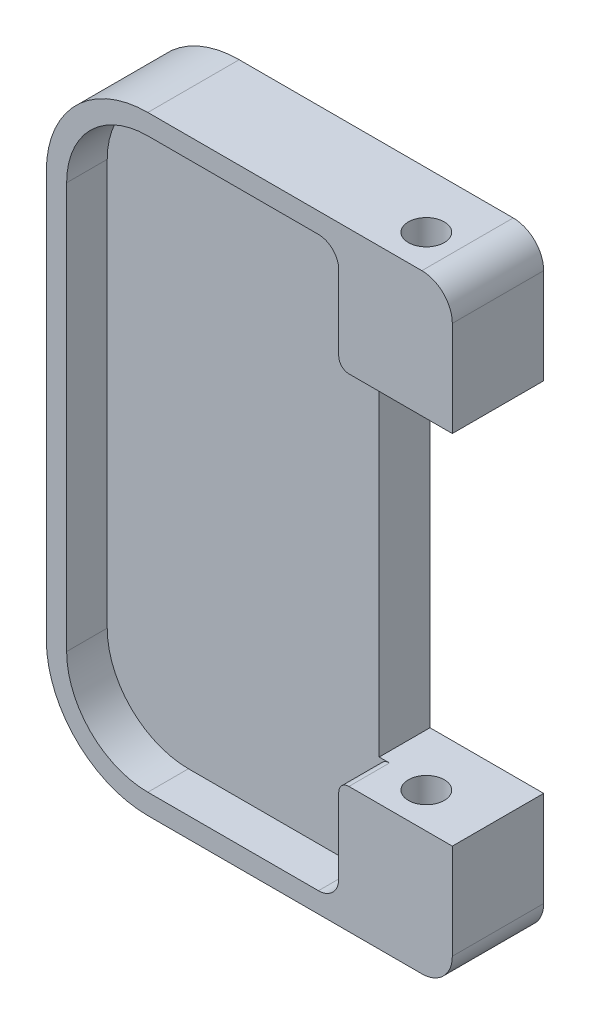
SolidWorks part; units mm, degrees
ref_plane "Front Plane" through (0, 0, 0) normal (0, 0, 1) x (1, 0, 0)
ref_plane "Top Plane" through (0, 0, 0) normal (0, 1, 0) x (1, 0, 0)
ref_plane "Right Plane" through (0, 0, 0) normal (1, 0, 0) x (0, 0, -1)
sketch "Sketch1" plane through (0, 0, 0) normal (0, 0, 1) x (1, 0, 0)
  line L1 (57.15, -22.225) -> (-57.15, -22.225)
  line L2 (57.15, -22.225) -> (57.15, 22.225)
  line L3 (57.15, 22.225) -> (-57.15, 22.225)
  line L4 (-57.15, -22.225) -> (-57.15, 22.225)
  line L5 (57.15, -22.225) -> (-57.15, 22.225) construction
  line L6 (57.15, 22.225) -> (-57.15, -22.225) construction
  point P0 (0, 0)
  dimension "D1" = 44.45
  dimension "D2" = 114.3
extrude "Boss-Extrude1" add sketch "Sketch1" along normal blind 62.23
sketch "Sketch2" plane through (0, 0, 62.23) normal (0, 0, 1) x (1, 0, 0)
  line L0 (-57.15, 22.225) -> (-57.15, -22.225) construction
  line L1 (57.15, -15.025) -> (-57.15, -15.025)
  line L2 (57.15, -15.025) -> (57.15, 15.025)
  line L3 (57.15, 15.025) -> (-57.15, 15.025)
  line L4 (-57.15, -15.025) -> (-57.15, 15.025)
  line L5 (57.15, -15.025) -> (-57.15, 15.025) construction
  line L6 (57.15, 15.025) -> (-57.15, -15.025) construction
  line L7 (57.15, 22.225) -> (-57.15, 22.225) construction
  point P0 (0, 0)
  dimension "D1" = 7.2
extrude "Cut-Extrude2" cut sketch "Sketch2" against normal blind 31.75
sketch "Sketch3" plane through (0, 0, 0) normal (0, 0, -1) x (-1, 0, 0)
  line L0 (-57.15, -22.225) -> (-57.15, 22.225) construction
  line L1 (57.15, 22.225) -> (-57.15, 22.225)
  line L2 (57.15, 22.225) -> (57.15, -9.525)
  line L3 (57.15, -9.525) -> (-57.15, -9.525)
  line L4 (-57.15, 22.225) -> (-57.15, -9.525)
  line L5 (57.15, -22.225) -> (-57.15, -22.225) construction
  dimension "D1" = 12.7
extrude "Cut-Extrude3" cut sketch "Sketch3" against normal blind 21.59
sketch "Sketch7" plane through (0, -22.225, 0) normal (0, -1, 0) x (1, 0, 0)
  line L0 (57.15, 62.23) -> (57.15, 0) construction
  line L1 (-57.15, 0) -> (57.15, 0) construction
  circle A0 centre (31.75, 50.36) radius 4.8
  circle A1 centre (-27.14, 39.37) radius 4.8
  dimension "D1" = 9.6
  dimension "D2" = 25.4
  dimension "D3" = 39.37
  dimension "D4" = 9.6
  dimension "D5" = 58.89
  dimension "D6" = 10.99
extrude "Cut-Extrude6" cut sketch "Sketch7" against normal up to surface (44.45 mm away) up to face at (0, 22.225, 41.91)
sketch "Sketch9" plane through (0, 0, 30.48) normal (0, 0, 1) x (1, 0, 0)
  line L5 (57.15, 15.025) -> (-57.15, 15.025) construction
  line L6 (-38.1, 15.025) -> (6.35, 15.025)
  line L7 (-38.1, 15.025) -> (-38.1, -15.025)
  line L8 (-38.1, -15.025) -> (6.35, -15.025)
  line L9 (6.35, 15.025) -> (6.35, -15.025)
  line L10 (-57.15, -15.025) -> (57.15, -15.025) construction
  line L11 (-57.15, 15.025) -> (-57.15, -15.025) construction
  line L12 (57.15, -15.025) -> (57.15, 15.025) construction
  dimension "D1" = 50.8
  dimension "25in" = 19.05
extrude "Cut-Extrude7" cut sketch "Sketch9" against normal through all both and the other way through all
sketch "Sketch16" plane through (0, -22.225, 0) normal (0, -1, 0) x (1, 0, 0)
  line L1 (-38.1, 30.48) -> (-57.15, 30.48) construction
  line L8 (-57.15, 62.23) -> (57.15, 62.23)
  line L9 (57.15, 62.23) -> (57.15, 47.0103)
  line L10 (57.15, 62.23) -> (57.15, 0) construction
  line L11 (-15.99, 39.37) -> (21.87, 50.36)
  line L12 (41.63, 50.36) -> (57.15, 47.0103)
  line L13 (-48.4121, 30.48) -> (-57.15, 30.48)
  line L15 (-57.15, 30.48) -> (-57.15, 62.23)
  arc A2 (41.63, 50.36) -> (21.87, 50.36) centre (31.75, 50.36) ccw
  arc A3 (-15.99, 39.37) -> (-38.2702, 40.0345) centre (-27.14, 39.37) ccw
  circle A4 centre (-27.14, 39.37) radius 4.8 construction
  circle A5 centre (31.75, 50.36) radius 4.8 construction
  arc A6 (-48.4121, 30.48) -> (-38.2702, 40.0345) centre (-48.4121, 40.64) ccw
  dimension "D1" = 6.35
  dimension "D2" = 5.08
  dimension "D3" = 10.16
extrude "Cut-Extrude8" cut sketch "Sketch16" against normal through all
sketch "Sketch14" plane through (6.35, 0, 0) normal (-1, 0, 0) x (0, 0, 1)
  line L0 (0, -15.025) -> (30.48, -15.025) construction
  line L1 (21.59, -9.525) -> (0, -9.525)
  line L2 (21.59, -9.525) -> (21.59, -15.025)
  line L3 (21.59, -15.025) -> (0, -15.025)
  line L4 (0, -9.525) -> (0, -15.025)
extrude "Boss-Extrude2" add sketch "Sketch14" along normal up to next
sketch "Sketch17" plane through (0, 0, 21.59) normal (0, 0, 1) x (1, 0, 0)
  line L1 (6.35, -15.025) -> (-38.1, -15.025)
  line L2 (6.35, -15.025) -> (6.35, -9.525)
  line L3 (6.35, -9.525) -> (-38.1, -9.525)
  line L4 (-38.1, -15.025) -> (-38.1, -9.525)
extrude "Boss-Extrude3" add sketch "Sketch17" along normal up to surface (8.89 mm away) up to face at (31.75, 0, 30.48)
sketch "Sketch18" plane through (-57.15, 0, 0) normal (-1, 0, 0) x (0, 0, 1)
  line L0 (30.48, 22.225) -> (30.48, -22.225) construction
  line L1 (21.59, 22.225) -> (30.48, 22.225)
  line L2 (21.59, 22.225) -> (21.59, -22.225)
  line L3 (21.59, -22.225) -> (30.48, -22.225)
  line L4 (30.48, 22.225) -> (30.48, -22.225)
  line L5 (21.59, 22.225) -> (30.48, -22.225) construction
  line L6 (21.59, -22.225) -> (30.48, 22.225) construction
  line L7 (30.48, -22.225) -> (0, -22.225) construction
  line L8 (21.59, -9.525) -> (21.59, 22.225) construction
  line L9 (30.48, 22.225) -> (21.59, 22.225) construction
  point P0 (26.035, 0)
sketch "Sketch20" plane through (0, 0, 21.59) normal (0, 0, -1) x (-1, 0, 0)
  line L0 (38.1, 15.025) -> (38.1, -9.525) construction
  line L1 (38.1, 38.1) -> (88.9, 38.1)
  line L2 (38.1, 38.1) -> (38.1, -38.1)
  line L3 (38.1, -38.1) -> (88.9, -38.1)
  line L4 (88.9, 38.1) -> (88.9, -38.1)
  line L5 (38.1, 38.1) -> (88.9, -38.1) construction
  line L6 (38.1, -38.1) -> (88.9, 38.1) construction
  point P0 (63.5, 0)
  point P9 (88.9, 0)
  dimension "D1" = 76.2
  dimension "D2" = 50.8
extrude "Boss-Extrude5" add sketch "Sketch20" against normal up to vertex (8.89 mm away)
fillet "Fillet4" radius 12.7 2 edges at (-88.9, -38.1, 26.035) (-88.9, 38.1, 26.035)
sketch "Sketch21" plane through (0, 0, 30.48) normal (0, 0, 1) x (1, 0, 0)
  line L0 (-40.64, -35.56) -> (-40.64, -24.765)
  line L9 (-76.2, -35.56) -> (-40.64, -35.56)
  line L16 (-50.9521, -12.485) -> (-40.64, -12.485)
  line L17 (-40.64, -12.485) -> (-40.64, -12.065)
  line L21 (-76.2, -35.56) -> (-40.64, -35.56)
  line L22 (-40.64, -35.56) -> (-40.64, -24.765)
  line L23 (-40.64, -24.765) -> (-50.9521, -24.765)
  line L24 (-40.64, -24.765) -> (-50.9521, -24.765)
  line L25 (-50.9521, -24.765) -> (-50.9521, -12.485)
  line L26 (-50.9521, -24.765) -> (-50.9521, -12.485)
  line L27 (-50.9521, 12.485) -> (-50.9521, 24.765)
  line L28 (-50.9521, 12.485) -> (-50.9521, 24.765)
  line L29 (-50.9521, 24.765) -> (-40.64, 24.765)
  line L30 (-50.9521, 24.765) -> (-40.64, 24.765)
  line L31 (-40.64, 24.765) -> (-40.64, 35.56)
  line L32 (-40.64, 24.765) -> (-40.64, 35.56)
  line L33 (-40.64, 35.56) -> (-76.2, 35.56)
  line L36 (-50.9521, -12.485) -> (54.61, -12.485)
  line L37 (54.61, -12.485) -> (54.61, 12.485)
  line L38 (54.61, 12.485) -> (8.89, 12.485)
  line L39 (8.89, 12.485) -> (8.89, -12.065)
  line L40 (8.89, -12.065) -> (-40.64, -12.065)
  line L41 (-40.64, -12.065) -> (-40.64, 12.485)
  line L42 (-40.64, 12.485) -> (-50.9521, 12.485)
  line L43 (-40.64, 35.56) -> (-76.2, 35.56)
  line L44 (-86.36, 25.4) -> (-86.36, -25.4)
  line L45 (-86.36, 25.4) -> (-86.36, -25.4)
  line L57 (-40.64, -12.065) -> (-40.64, 12.485)
  line L58 (-40.64, 12.485) -> (-50.9521, 12.485)
  arc A9 (-76.2, 35.56) -> (-86.36, 25.4) centre (-76.2, 25.4) ccw
  arc A10 (-76.2, 35.56) -> (-86.36, 25.4) centre (-76.2, 25.4) ccw
  arc A11 (-86.36, -25.4) -> (-76.2, -35.56) centre (-76.2, -25.4) ccw
  arc A16 (-86.36, -25.4) -> (-76.2, -35.56) centre (-76.2, -25.4) ccw
  dimension "D1" = 2.54
extrude "Cut-Extrude10" cut sketch "Sketch21" against normal blind 2.54
sketch "Sketch22" plane through (0, -22.225, 0) normal (0, -1, 0) x (1, 0, 0)
  line L0 (-57.15, 0) -> (57.15, 0)
  line L1 (57.15, 0) -> (57.15, 47.0103)
  line L2 (57.15, 47.0103) -> (41.63, 50.36)
  line L3 (-15.99, 39.37) -> (21.87, 50.36)
  line L4 (-57.15, 0) -> (-57.15, 21.59)
  line L5 (-57.15, 21.59) -> (-38.1, 21.59)
  line L6 (-38.1, 21.59) -> (-38.1, 30.48)
  line L7 (-38.1, 30.48) -> (-38.2702, 40.0345)
  arc A0 (-15.99, 39.37) -> (-38.2395, 38.3096) centre (-27.14, 39.37) ccw
  arc A1 (41.63, 50.36) -> (21.87, 50.36) centre (31.75, 50.36) ccw
  point P12 (-57.15, 21.59)
  point P16 (-27.14, 39.37)
  point P23 (31.75, 50.36)
  circle M1 centre (-27.14, 39.37) radius 4.8
  circle M2 centre (31.75, 50.36) radius 4.8
  line M4 (-38.1, 30.48) -> (-38.1, 21.59)
  line M5 (-38.1, 21.59) -> (-57.15, 21.59)
  line M6 (-57.15, 21.59) -> (-57.15, 0)
  line M7 (-57.15, 0) -> (57.15, 0)
  line M8 (57.15, 0) -> (57.15, 47.0103)
  line M9 (57.15, 47.0103) -> (41.63, 50.36)
  arc M10 (41.63, 50.36) -> (21.87, 50.36) centre (31.75, 50.36) ccw
  line M11 (21.87, 50.36) -> (-15.99, 39.37)
  arc M12 (-15.99, 39.37) -> (-38.2702, 40.0345) centre (-27.14, 39.37) ccw
extrude "Cut-Extrude11" cut sketch "Sketch22" against normal through all both and the other way through all contours L7 M4 M5 M6 M7 M8 M9 M10 M11 M12 M2 M1
sketch "Sketch25" plane through (0, 0, 30.48) normal (0, 0, 1) x (1, 0, 0)
  line L1 (-48.4121, 22.225) -> (-38.1, 22.225)
  line L2 (-48.4121, 22.225) -> (-48.4121, 15.025)
  line L3 (-48.4121, 15.025) -> (-38.1, 15.025)
  line L4 (-38.1, 22.225) -> (-38.1, 15.025)
  line L5 (-48.4121, -15.025) -> (-38.1, -15.025)
  line L6 (-48.4121, -15.025) -> (-48.4121, -22.225)
  line L7 (-48.4121, -22.225) -> (-38.1, -22.225)
  line L8 (-38.1, -15.025) -> (-38.1, -22.225)
extrude "Cut-Extrude14" cut sketch "Sketch25" along normal blind 17.272 contours L6 L7 L8 L5
sketch "Sketch26" plane through (0, 0, 30.48) normal (0, 0, 1) x (1, 0, 0)
  line L1 (-48.4121, 22.225) -> (-38.1, 22.225)
  line L2 (-48.4121, 22.225) -> (-48.4121, 15.025)
  line L3 (-48.4121, 15.025) -> (-38.1, 15.025)
  line L4 (-38.1, 22.225) -> (-38.1, 15.025)
extrude "Cut-Extrude15" cut sketch "Sketch26" along normal blind 17.272
sketch "Sketch28" plane through (0, 0, 30.48) normal (0, 0, 1) x (1, 0, 0)
  line L0 (-40.64, -24.765) -> (-50.9521, -24.765)
  line L3 (-38.1, -38.1) -> (-76.2, -38.1) construction
  line L4 (-40.64, -35.56) -> (-50.9521, -35.56)
  line L5 (-76.2, -35.56) -> (-40.64, -35.56) construction
  line L6 (-40.64, -38.1) -> (-50.9521, -38.1)
  point P3 (-40.64, -38.1)
  point P18 (-50.9521, -24.765)
  point P19 (-50.9521, -35.56)
  point P21 (-50.9521, -38.1)
sketch "Sketch32" plane through (0, -38.1, 0) normal (0, -1, 0) x (1, 0, 0)
  line L0 (-50.9521, 30.48) -> (-40.64, 30.48)
  line L1 (-38.1, 30.48) -> (-38.1, 21.59) construction
  circle A0 centre (-45.7961, 26.035) radius 2.2479
  point P0 (-40.64, 30.48)
  point P1 (-50.9521, 30.48)
  point P6 (-45.7961, 30.48)
  point P9 (-38.1, 26.035)
  dimension "D1" = 4.4958
extrude "Cut-Extrude16" cut sketch "Sketch32" against normal through all both and the other way through all contours A0
fillet "Fillet5" radius 3.81 2 edges at (-38.1, 38.1, 26.035) (-38.1, -38.1, 26.035)
sketch "Sketch33" plane through (0, 0, 30.48) normal (0, 0, 1) x (1, 0, 0)
  line L0 (-38.1, 34.29) -> (-38.1, -34.29) construction
  line L1 (-38.1, 0) -> (-38.1, 22.352)
  line L2 (-38.1, 0) -> (-38.1, -22.352)
  line L4 (-38.1, 22.352) -> (-53.467, 22.352)
  line L5 (-38.1, 22.352) -> (-38.1, -22.352)
  line L6 (-38.1, -22.352) -> (-53.467, -22.352)
  line L7 (-53.467, 22.352) -> (-53.467, -22.352)
  line L8 (-53.467, 22.352) -> (-38.1, 22.352)
  line L9 (-53.467, 22.352) -> (-53.467, -22.352)
  line L10 (-53.467, -22.352) -> (-38.1, -22.352)
  line L11 (-38.1, 22.352) -> (-38.1, -22.352)
  point P0 (-38.1, 0)
  line M4 (-38.1, -34.29) -> (-38.1, 34.29)
  line M18 (-50.9521, 12.485) -> (-40.64, 12.485)
  line M19 (-40.64, 12.485) -> (-40.64, -12.485)
  line M20 (-40.64, -12.485) -> (-50.9521, -12.485)
  dimension "D1" = 22.352
  dimension "D2" = 22.352
  dimension "D3" = 15.367
extrude "Cut-Extrude22" cut sketch "Sketch33" against normal through all contours L4 L7 L6 M18 M19 M20 M4 | L7 M18 M20 M19
sketch "Sketch38" plane through (0, -35.56, 0) normal (0, 1, 0) x (1, 0, 0)
  line L0 (-46.9894, -27.94) -> (-47.6244, -27.94)
  line L1 (-76.2, -27.94) -> (-46.9894, -27.94) construction
  line L2 (-44.6027, -27.94) -> (-43.9677, -27.94)
  line L3 (-44.6027, -27.94) -> (-40.64, -27.94) construction
  arc A0 (-44.6027, -27.94) -> (-46.9894, -27.94) centre (-45.7961, -26.7924) cw
  arc A1 (-43.9677, -27.94) -> (-47.6244, -27.94) centre (-45.7961, -26.1768) cw
  point P0 (-44.6027, -27.94)
  point P1 (-46.9894, -27.94)
  point P10 (-45.7961, -28.448)
  point P14 (-45.7961, -29.083)
  point P15 (-45.7961, -29.083)
  dimension "D4" = 2.54
  dimension "D1" = 0.635
  dimension "D2" = 0.635
  dimension "D3" = 0.635
sketch "Sketch39" plane through (0, 35.56, 0) normal (0, -1, 0) x (1, 0, 0)
  line L0 (-46.9894, 27.94) -> (-47.6244, 27.94)
  line L1 (-46.9894, 27.94) -> (-76.2, 27.94) construction
  line L2 (-44.6027, 27.94) -> (-43.9677, 27.94)
  line L3 (-40.64, 27.94) -> (-44.6027, 27.94) construction
  arc A0 (-46.9894, 27.94) -> (-44.6027, 27.94) centre (-45.7961, 26.7924) cw
  arc A1 (-47.6244, 27.94) -> (-43.9677, 27.94) centre (-45.7961, 26.1768) cw
  point P0 (-46.9894, 27.94)
  point P1 (-44.6027, 27.94)
  point P10 (-45.7961, 28.448)
  point P14 (-45.7961, 29.083)
  dimension "D4" = 2.54
  dimension "D1" = 0.635
  dimension "D2" = 0.635
  dimension "D3" = 0.635
sketch "Sketch41" plane through (0, -24.765, 0) normal (0, -1, 0) x (1, 0, 0)
  line L0 (-44.6027, 27.94) -> (-40.64, 27.94)
  line L1 (-50.9521, 30.48) -> (-40.64, 30.48)
  line L2 (-50.9521, 30.48) -> (-50.9521, 27.94)
  line L3 (-50.9521, 27.94) -> (-46.9894, 27.94)
  line L4 (-40.64, 30.48) -> (-40.64, 27.94)
  arc A0 (-46.9894, 27.94) -> (-44.6027, 27.94) centre (-45.7961, 25.8427) cw
  point P6 (-46.9894, 27.94)
  point P7 (-44.6027, 27.94)
extrude "Boss-Extrude6" add sketch "Sketch41" along normal blind 10.922
sketch "Sketch44" plane through (0, 24.765, 0) normal (0, 1, 0) x (1, 0, 0)
  line L0 (-44.6027, -27.94) -> (-40.64, -27.94)
  line L1 (-50.9521, -27.94) -> (-46.9894, -27.94)
  line L2 (-50.9521, -27.94) -> (-50.9521, -30.48)
  line L3 (-50.9521, -30.48) -> (-40.64, -30.48)
  line L4 (-40.64, -27.94) -> (-40.64, -30.48)
  arc A0 (-44.6027, -27.94) -> (-46.9894, -27.94) centre (-45.7961, -25.8427) cw
  point P6 (-44.6027, -27.94)
  point P7 (-46.9894, -27.94)
extrude "Boss-Extrude7" add sketch "Sketch44" along normal blind 10.922
sketch "Sketch45" plane through (0, 0, 21.59) normal (0, 0, -1) x (-1, 0, 0)
  line L0 (53.467, 22.352) -> (53.467, -22.352)
  line L2 (41.91, -38.1) -> (76.2, -38.1) construction
  line L3 (53.467, -38.1) -> (76.2, -38.1)
  line L5 (76.2, 38.1) -> (41.91, 38.1) construction
  line L6 (53.467, 38.1) -> (76.2, 38.1)
  line L7 (88.9, -25.4) -> (88.9, 25.4)
  line L8 (53.467, 38.1) -> (53.467, 22.352)
  line L9 (53.467, -22.352) -> (53.467, -38.1)
  arc A0 (76.2, 38.1) -> (88.9, 25.4) centre (76.2, 25.4) cw
  arc A1 (88.9, -25.4) -> (76.2, -38.1) centre (76.2, -25.4) cw
extrude "Boss-Extrude8" add sketch "Sketch45" along normal blind 2.54
sketch "Sketch47" plane through (0, 0, 27.94) normal (0, 0, 1) x (1, 0, 0)
  line L1 (-53.467, 22.352) -> (-53.467, -22.352)
  line L5 (-86.36, 25.4) -> (-86.36, -25.4)
  line L8 (-76.2, 35.56) -> (-50.9521, 35.56)
  line L9 (-50.9521, 35.56) -> (-50.9521, 22.352)
  line L10 (-50.9521, 22.352) -> (-53.467, 22.352)
  line L14 (-50.9521, -22.352) -> (-53.467, -22.352)
  line L15 (-50.9521, -22.352) -> (-50.9521, -35.56)
  line L16 (-50.9521, -35.56) -> (-76.2, -35.56)
  arc A2 (-76.2, -35.56) -> (-86.36, -25.4) centre (-76.2, -25.4) cw
  arc A3 (-76.2, 35.56) -> (-86.36, 25.4) centre (-76.2, 25.4) ccw
  dimension "D1" = 10.16
  dimension "D2" = 10.16
extrude "Cut-Extrude23" cut sketch "Sketch47" against normal blind 2.54
sketch "Sketch49" plane through (-53.467, 0, 0) normal (1, 0, 0) x (0, 0, -1)
  line L0 (-21.59, 38.1) -> (-19.05, 38.1)
  line L1 (-19.05, 38.1) -> (-19.05, -38.1)
  line L2 (-19.05, -38.1) -> (-21.59, -38.1)
  line L3 (-21.59, -38.1) -> (-21.59, -22.352)
  line L4 (-21.59, 38.1) -> (-21.59, 22.352)
  line L5 (-21.59, 22.352) -> (-25.4, 22.352)
  line L6 (-25.4, 22.352) -> (-25.4, -22.352)
  line L7 (-25.4, -22.352) -> (-21.59, -22.352)
extrude "Boss-Extrude10" add sketch "Sketch49" along normal blind 1.143
sketch "Sketch54" plane through (0, 0, 19.05) normal (0, 0, -1) x (-1, 0, 0)
  line L0 (38.1, 22.352) -> (52.324, 22.352)
  line L1 (52.324, 22.352) -> (52.324, 38.1)
  line L2 (52.324, 38.1) -> (41.91, 38.1)
  line L3 (38.1, 22.352) -> (38.1, 34.29)
  line L4 (38.1, 34.29) -> (38.1, 22.352) construction
  line L5 (41.91, -38.1) -> (52.324, -38.1)
  line L6 (52.324, -38.1) -> (52.324, -22.352)
  line L7 (52.324, -22.352) -> (38.1, -22.352)
  line L8 (38.1, -22.352) -> (38.1, -34.29)
  arc A0 (41.91, 38.1) -> (38.1, 34.29) centre (41.91, 34.29) ccw construction
  arc A1 (38.1, 34.29) -> (41.91, 38.1) centre (41.91, 34.29) cw
  arc A2 (38.1, -34.29) -> (41.91, -38.1) centre (41.91, -34.29) ccw
extrude "Boss-Extrude13" add sketch "Sketch54" against normal blind 2.54
sketch "Sketch55" plane through (-52.324, 0, 0) normal (1, 0, 0) x (0, 0, -1)
  line L1 (-25.4, 22.352) -> (-19.05, 22.352)
  line L2 (-25.4, 22.352) -> (-25.4, -22.352)
  line L3 (-25.4, -22.352) -> (-19.05, -22.352)
  line L4 (-19.05, 22.352) -> (-19.05, -22.352)
sketch "Sketch59" plane through (-50.9521, 0, 0) normal (-1, 0, 0) x (0, 0, 1)
  line L1 (30.48, 35.56) -> (25.4, 35.56)
  line L2 (30.48, 35.56) -> (30.48, 22.352)
  line L3 (30.48, 22.352) -> (25.4, 22.352)
  line L4 (25.4, 35.56) -> (25.4, 22.352)
  line L5 (25.4, -22.352) -> (30.48, -22.352)
  line L6 (25.4, -22.352) -> (25.4, -35.56)
  line L7 (25.4, -35.56) -> (30.48, -35.56)
  line L8 (30.48, -22.352) -> (30.48, -35.56)
extrude "Boss-Extrude16" add sketch "Sketch59" along normal blind 1.3589
fillet "Fillet6" radius 2.54 2 edges at (-52.311, -35.56, 27.94) (-52.311, 35.56, 27.94)
fillet "Fillet7" radius 1.27 2 edges at (-52.311, -22.352, 27.94) (-52.311, 22.352, 27.94)
